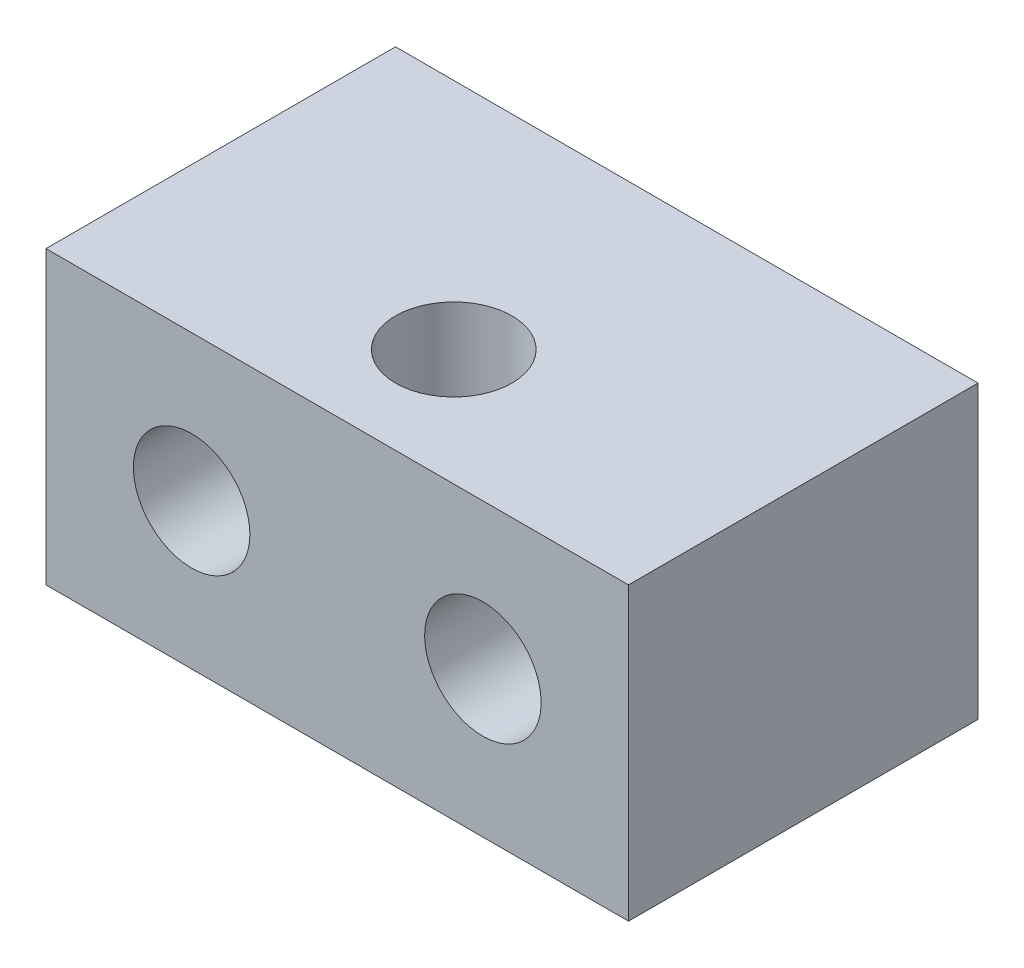
SolidWorks part; units mm, degrees
ref_plane "前视基准面" through (0, 0, 0) normal (0, 0, 1) x (1, 0, 0)
ref_plane "上视基准面" through (0, 0, 0) normal (0, 1, 0) x (1, 0, 0)
ref_plane "右视基准面" through (0, 0, 0) normal (1, 0, 0) x (0, 0, -1)
sketch "草图1" plane through (0, 0, 0) normal (0, 1, 0) x (1, 0, 0)
  line L1 (-10, 6) -> (10, 6)
  line L2 (-10, 6) -> (-10, -6)
  line L3 (-10, -6) -> (10, -6)
  line L4 (10, 6) -> (10, -6)
  circle A0 centre (0, -2) radius 2
  point P4 (0, 6)
  point P6 (10, 0)
  point P9 (0, 0)
  point P10 (0, -1.1437)
  dimension "D3" = 4
  dimension "D1" = 12
  dimension "D2" = 20
  dimension "D4" = 2
extrude "凸台-拉伸1" add sketch "草图1" along normal mid plane 10
sketch "草图2" plane through (0, 0, 0) normal (0, 0, 1) x (1, 0, 0)
  line L0 (0, 5) -> (0, -5) construction
  line L1 (-10, 5) -> (10, 5) construction
  line L2 (-10, -5) -> (10, -5) construction
  line L3 (-10, 5) -> (-10, -5) construction
  circle A0 centre (-5, 0) radius 2
  circle A1 centre (5, 0) radius 2
  point P10 (0, 0)
  dimension "D1" = 4
  dimension "D2" = 5
extrude "切除-拉伸1" cut sketch "草图2" against normal through all both and the other way through all
